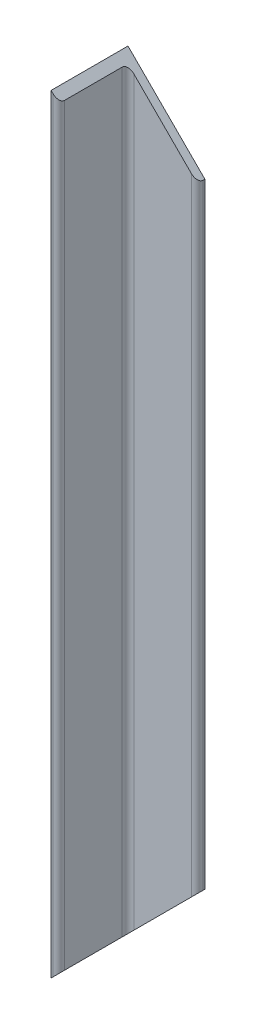
SolidWorks part; units mm, degrees
material "ASTM A36 Steel"
ref_plane "Front Plane" through (0, 0, 0) normal (0, 0, 1) x (1, 0, 0)
ref_plane "Top Plane" through (0, 0, 0) normal (0, 1, 0) x (1, 0, 0)
ref_plane "Right Plane" through (0, 0, 0) normal (1, 0, 0) x (0, 0, -1)
sketch "Sketch1" plane through (0, 0, 0) normal (0, 1, 0) x (1, 0, 0)
  line L0 (-27.4999, 29.2132) -> (-67.4999, 29.2132)
  line L1 (-67.4999, 29.2132) -> (-67.4999, -10.7868)
  line L2 (-67.4999, -10.7868) -> (-66.4999, -10.7868)
  line L3 (-63.4999, -7.7868) -> (-63.4999, 22.2132)
  line L4 (-60.4999, 25.2132) -> (-30.4999, 25.2132)
  line L5 (-27.4999, 28.2132) -> (-27.4999, 29.2132)
  arc A0 (-66.4999, -10.7868) -> (-63.4999, -7.7868) centre (-66.4999, -7.7868) ccw
  arc A1 (-63.4999, 22.2132) -> (-60.4999, 25.2132) centre (-60.4999, 22.2132) cw
  arc A2 (-30.4999, 25.2132) -> (-27.4999, 28.2132) centre (-30.4999, 28.2132) ccw
  point P8 (-63.4999, -10.7868)
  point P13 (-27.4999, 25.2132)
  dimension "D5" = 3
  dimension "D1" = 40
  dimension "D2" = 40
  dimension "D3" = 4
  dimension "D4" = 4
extrude "Boss-Extrude1" add sketch "Sketch1" along normal blind 400
sketch "Sketch2" plane through (0, 0, -29.2132) normal (0, 0, -1) x (-1, 0, 0)
  line L0 (67.4999, 0) -> (27.4999, 40)
  line L1 (27.4999, 400) -> (27.4999, 0) construction
  line L2 (27.4999, 40) -> (27.4999, 0)
  line L3 (27.4999, 0) -> (67.4999, 0)
  line L4 (27.4999, 400) -> (67.4999, 400) construction
  line L6 (27.4999, 400) -> (67.4999, 400)
  line L7 (27.4999, 360) -> (27.4999, 400)
  line L8 (67.4999, 400) -> (27.4999, 360)
  dimension "D1" = 40
  dimension "D2" = 0
extrude "Cut-Extrude1" cut sketch "Sketch2" against normal through all both and the other way through all
